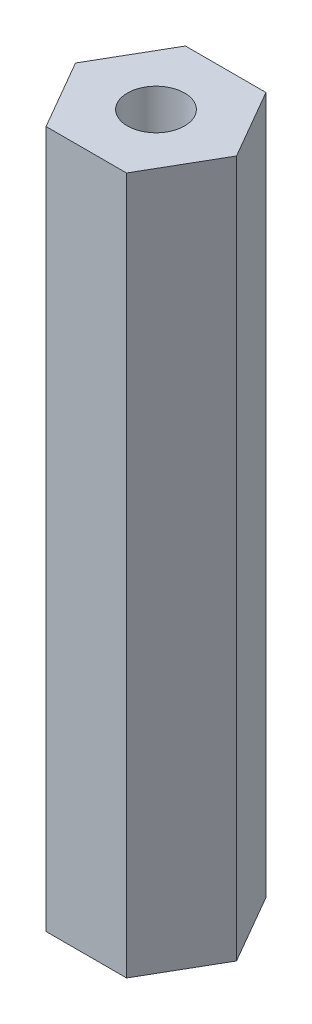
SolidWorks part; units mm, degrees
ref_plane "前视基准面" through (0, 0, 0) normal (0, 0, 1) x (1, 0, 0)
ref_plane "上视基准面" through (0, 0, 0) normal (0, 1, 0) x (1, 0, 0)
ref_plane "右视基准面" through (0, 0, 0) normal (1, 0, 0) x (0, 0, -1)
ref_plane "基准面4" through (0, 0, 0) normal (0, -1, 0) x (1, 0, 0)
sketch "草图1" plane through (0, 0, 0) normal (0, -1, 0) x (1, 0, 0)
  line L0 (-1.4434, -2.5) -> (1.4434, -2.5)
  line L1 (1.4434, -2.5) -> (2.8868, 0)
  line L2 (2.8868, 0) -> (1.4434, 2.5)
  line L3 (1.4434, 2.5) -> (-1.4434, 2.5)
  line L4 (-1.4434, 2.5) -> (-2.8868, 0)
  line L5 (-2.8868, 0) -> (-1.4434, -2.5)
  circle A0 centre (0, 0) radius 1.025
extrude "凸台-拉伸1" add sketch "草图1" against normal blind 25
